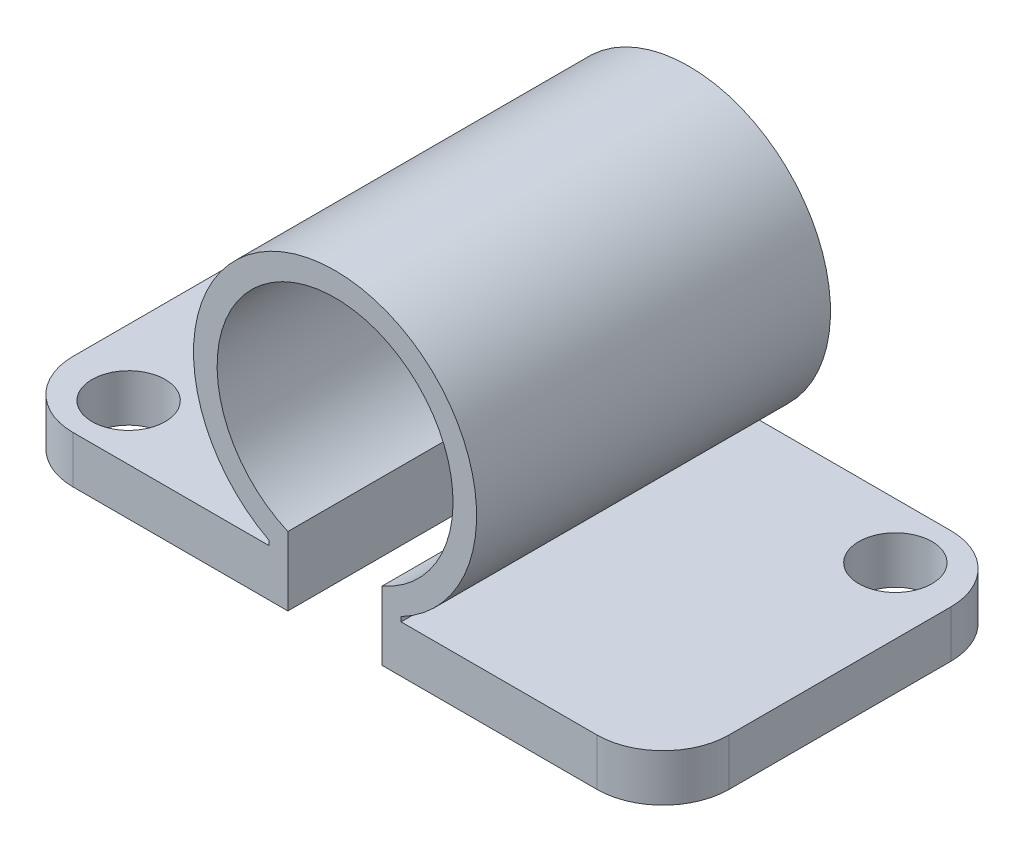
SolidWorks part; units mm, degrees
ref_plane "Alzado" through (0, 0, 0) normal (0, 0, 1) x (1, 0, 0)
ref_plane "Planta" through (0, 0, 0) normal (0, 1, 0) x (1, 0, 0)
ref_plane "Vista lateral" through (0, 0, 0) normal (1, 0, 0) x (0, 0, -1)
sketch "Croquis2" plane through (0, 0, 0) normal (0, 0, 1) x (1, 0, 0)
  line L0 (-1, 0) -> (1, 0) construction
  line L1 (2.8, -5.3066) -> (2.8, -5.5)
  line L2 (-2.8, -5.3066) -> (-2.8, -5.5)
  line L3 (0, 0) -> (0, -8) construction
  line L5 (-2.8, -5.5) -> (-2, -5.5)
  line L6 (-2, -5.5) -> (-2, -4.5826)
  line L7 (2.8, -5.5) -> (2, -5.5)
  line L8 (2, -5.5) -> (2, -4.5826)
  arc A0 (2.8, -5.3066) -> (-2.8, -5.3066) centre (0, 0) ccw
  arc A4 (2, -4.5826) -> (-2, -4.5826) centre (0, 0) ccw
  point P7 (0, 0)
  point P13 (0, -8)
  dimension "D1" = 5
  dimension "D2" = 12
  dimension "D3" = 11
  dimension "D6" = 2
  dimension "D9" = 8
  dimension "D4" = 2
  dimension "D5" = 0.8
  dimension "D7" = 2
  dimension "D8" = 0.8
extrude "Saliente-Extruir2" add sketch "Croquis2" along normal blind 15
sketch "Croquis3" plane through (0, -5.5, 0) normal (0, -1, 0) x (1, 0, 0)
  line L0 (0, 0) -> (0, 15) construction
  line L1 (-5, 0) -> (5, 0) construction
  line L2 (5, 15) -> (-5, 15) construction
  line L3 (11.1, 7.5) -> (-11.1, 7.5) construction
  line L8 (-11.1, 2.35) -> (-11.1, 12.65) construction
  line L9 (11.1, 2.35) -> (11.1, 12.65) construction
  line L10 (2, 0) -> (2, 15)
  line L11 (11.1, 0) -> (2, 0)
  line L12 (13.9, 2.8) -> (13.9, 12.2)
  line L13 (11.1, 15) -> (2, 15)
  line L14 (-13.9, 2.8) -> (-13.9, 12.2)
  line L15 (13.9, 0) -> (-13.9, 15) construction
  line L16 (13.9, 15) -> (-13.9, 0) construction
  line L17 (-2, 0) -> (-2, 15)
  line L18 (-2, 0) -> (-11.1, 0)
  line L19 (-2, 15) -> (-11.1, 15)
  arc A2 (13.9, 12.2) -> (11.1, 15) centre (11.1, 12.2) ccw
  arc A3 (-11.1, 15) -> (-13.9, 12.2) centre (-11.1, 12.2) ccw
  arc A4 (-13.9, 2.8) -> (-11.1, 0) centre (-11.1, 2.8) ccw
  arc A5 (13.9, 2.8) -> (11.1, 0) centre (11.1, 2.8) cw
  circle A6 centre (11.1, 2.35) radius 1.55
  circle A7 centre (-11.1, 12.65) radius 1.55
  point P6 (0, 7.5)
  point P11 (11.1, 7.5)
  point P14 (0, 7.5)
  point P17 (-11.1, 7.5)
  point P18 (0, 7.5)
  dimension "D1" = 10.3
  dimension "D6" = 2.8
  dimension "D3" = 22.2
  dimension "D4" = 10.3
  dimension "D5" = 27.8
extrude "Saliente-Extruir3" add sketch "Croquis3" along normal blind 2
